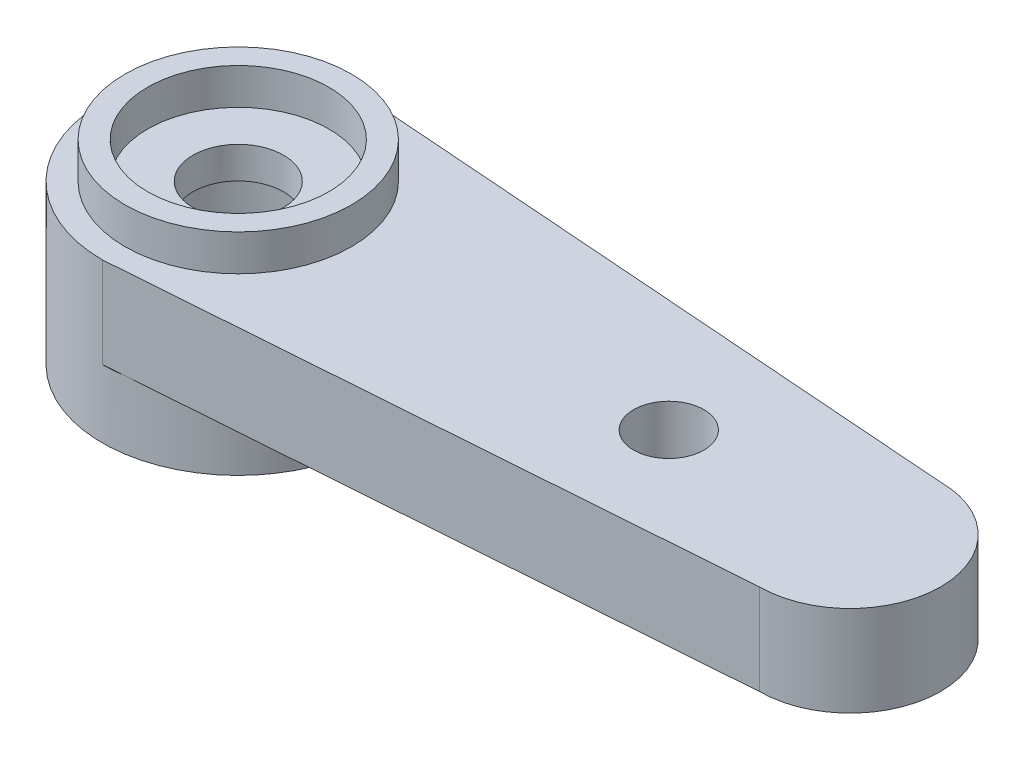
SolidWorks part; units mm, degrees
ref_plane "Спереди" through (0, 0, 0) normal (0, 0, 1) x (1, 0, 0)
ref_plane "Сверху" through (0, 0, 0) normal (0, 1, 0) x (1, 0, 0)
ref_plane "Справа" through (0, 0, 0) normal (1, 0, 0) x (0, 0, -1)
sketch "Эскиз2" plane through (0, 0, 0) normal (0, 1, 0) x (1, 0, 0)
  line L0 (-3, 0) -> (15.5, 0)
  line L1 (0, 3) -> (13.5, 2)
  line L2 (13.5, -2) -> (0, -3)
  circle A0 centre (0, 0) radius 3
  circle A1 centre (13.5, 0) radius 2
  dimension "D1" = 18.5
  dimension "D2" = 6
  dimension "D3" = 4
extrude "Бобышка-Вытянуть1" add sketch "Эскиз2" along normal blind 2 contours A1 L1 A0 L0 | L0 A0 L1 | L2 A0 L0 | A1 L0 A0 L2 | A1 L0 | L0 A1
sketch "Эскиз3" plane through (0, 2, 0) normal (0, 1, 0) x (1, 0, 0)
  circle A0 centre (0, 0) radius 2.5
  dimension "D1" = 5
extrude "Бобышка-Вытянуть2" add sketch "Эскиз3" along normal blind 0.8
sketch "Эскиз4" plane through (0, 0, 0) normal (0, -1, 0) x (1, 0, 0)
  circle A0 centre (0, 0) radius 3
extrude "Бобышка-Вытянуть3" add sketch "Эскиз4" along normal blind 1.5
sketch "Эскиз5" plane through (0, -1.5, 0) normal (0, -1, 0) x (-1, 0, 0)
  circle A0 centre (0, 0) radius 2
extrude "Вырез-Вытянуть1" cut sketch "Эскиз5" against normal blind 2.8
sketch "Эскиз6" plane through (0, 2.8, 0) normal (0, 1, 0) x (1, 0, 0)
  circle A0 centre (0, 0) radius 2
extrude "Вырез-Вытянуть2" cut sketch "Эскиз6" along direction (0, -1, 0) on the side against the normal up to vertex (0.8 mm away)
sketch "Эскиз7" plane through (0, 2, 0) normal (0, 1, 0) x (1, 0, 0)
  circle A0 centre (0, 0) radius 1
  dimension "D1" = 2
extrude "Вырез-Вытянуть3" cut sketch "Эскиз7" against normal through all
sketch "Эскиз8" plane through (0, 2, 0) normal (0, 1, 0) x (1, 0, 0)
  line L0 (0, 0) -> (9.5, 0)
  circle A0 centre (9.5, 0) radius 0.775
extrude "Вырез-Вытянуть4" cut sketch "Эскиз8" against normal through all
